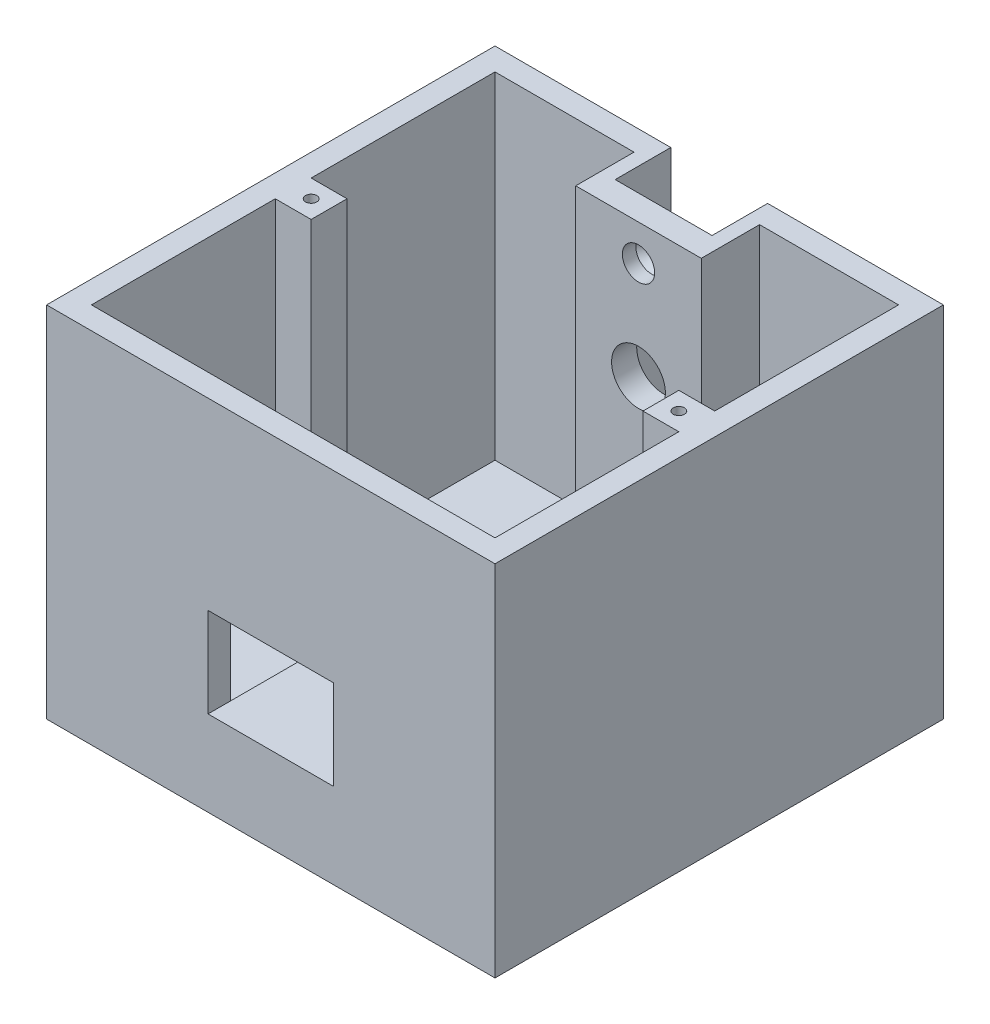
SolidWorks part; units mm, degrees
ref_plane "Front Plane" through (0, 0, 0) normal (0, 0, 1) x (1, 0, 0)
ref_plane "Top Plane" through (0, 0, 0) normal (0, 1, 0) x (1, 0, 0)
ref_plane "Right Plane" through (0, 0, 0) normal (1, 0, 0) x (0, 0, -1)
sketch "Sketch1" plane through (0, 0, 0) normal (0, 1, 0) x (1, 0, 0)
  line L1 (-25, -25) -> (25, -25)
  line L2 (-25, -25) -> (-25, 25)
  line L3 (-25, 25) -> (25, 25)
  line L4 (25, -25) -> (25, 25)
  line L5 (-25, -25) -> (25, 25) construction
  line L6 (-25, 25) -> (25, -25) construction
  point P0 (0, 0)
  dimension "D1" = 50
  dimension "D2" = 50
extrude "Boss-Extrude1" add sketch "Sketch1" along normal blind 40
shell "Shell1" thickness 2.5
sketch "Sketch2" plane through (0, 2.5, 0) normal (0, 1, 0) x (1, 0, 0)
  line L0 (22.5, 22.5) -> (-22.5, 22.5) construction
  line L1 (-7, 22.5) -> (7, 22.5)
  line L2 (-7, 22.5) -> (-7, -22.5)
  line L3 (-7, -22.5) -> (7, -22.5)
  line L4 (7, 22.5) -> (7, -22.5)
  line L5 (-22.5, -22.5) -> (22.5, -22.5) construction
  line L6 (22.5, 22.5) -> (-22.5, 22.5) construction
  point P10 (0, 22.5)
  point P11 (0, 22.5)
  dimension "D1" = 14
extrude "Boss-Extrude2" add sketch "Sketch2" along normal blind 7
sketch "Sketch4" plane through (0, 0, 0) normal (0, -1, 0) x (1, 0, 0)
  line L1 (-5.4, -15.1) -> (5.4, -15.1)
  line L2 (-5.4, -15.1) -> (-5.4, 15.1)
  line L3 (-5.4, 15.1) -> (5.4, 15.1)
  line L4 (5.4, -15.1) -> (5.4, 15.1)
  line L5 (-5.4, -15.1) -> (5.4, 15.1) construction
  line L6 (-5.4, 15.1) -> (5.4, -15.1) construction
  point P0 (0, 0)
  dimension "D1" = 30.2
  dimension "D2" = 10.8
extrude "Cut-Extrude1" cut sketch "Sketch4" against normal blind 6.2
sketch "Sketch5" plane through (0, 9.5, 0) normal (0, 1, 0) x (1, 0, 0)
  line L0 (-22.5, 0) -> (22.5, 0) construction
  line L1 (-22.5, 22.5) -> (-22.5, -22.5) construction
  line L2 (22.5, -22.5) -> (22.5, 22.5) construction
  line L3 (0, 11) -> (0, 0)
  line L4 (0, 0) -> (0, -11)
  point P6 (-35.5268, 3.9045)
  point P8 (0, 0)
  dimension "D1" = 11
hole_wizard "CSK SLOT for M1.6 Countersunk Flat Head Screw1" positions "Sketch6" profile "Sketch7" size "M1.6" standard "ISO" slot yes end condition through all
sketch "Sketch6" plane through (0, 9.5, 0) normal (0, 1, 0) x (1, 0, 0)
  point P0 (0, 11)
  point P3 (0, -11)
sketch "Sketch7" plane through (0, 9.5, -11) normal (1, 0, 0) x (0, 0, 1)
  line L0 (0, 0) -> (0, 9.5)
  line L1 (0, 9.5) -> (0.9, 9.5)
  line L2 (0.9, 9.5) -> (0.9, 2.9)
  line L3 (0.9, 2.9) -> (1.8, 2)
  line L4 (1.8, 2) -> (1.8, 0)
  line L6 (1.8, 0) -> (0, 0)
  line L7 (-0.9, 2.9) -> (-1.8, 2) construction
  line L11 (0, -6.35) -> (0, 107.95) construction
  dimension "Thru Hole Dia." = 1.8
  dimension "Thru Hole Depth" = 9.5
  dimension "C'Sink Dia." = 3.6
  dimension "C'Sink Angle" = 90
  dimension "Head Clearance" = 2
sketch "Sketch8" plane through (0, 2.5, 0) normal (0, 1, 0) x (1, 0, 0)
  line L0 (-22.5, 0) -> (22.5, 0) construction
  line L1 (19.5, -1.5) -> (16.5, -1.5)
  line L2 (19.5, -1.5) -> (19.5, 1.5)
  line L3 (19.5, 1.5) -> (16.5, 1.5)
  line L4 (16.5, -1.5) -> (16.5, 1.5)
  line L5 (19.5, -1.5) -> (16.5, 1.5) construction
  line L6 (19.5, 1.5) -> (16.5, -1.5) construction
  line L7 (22.5, -22.5) -> (22.5, 22.5) construction
  point P0 (18, 0)
  dimension "D1" = 3
  dimension "D2" = 3
  dimension "D3" = 3
extrude "Cut-Extrude2" [suppressed] cut sketch "Sketch8" against normal through all
sketch "Sketch9" plane through (-22.5, 0, 0) normal (1, 0, 0) x (0, 0, -1)
  line L0 (0, 2.5) -> (0, 40) construction
  line L1 (22.5, 2.5) -> (-22.5, 2.5) construction
  line L2 (22.5, 40) -> (-22.5, 40) construction
  line L4 (-7, 2.5) -> (7, 2.5)
  line L5 (-7, 2.5) -> (-7, 40)
  line L6 (-7, 40) -> (7, 40)
  line L7 (7, 2.5) -> (7, 40)
  point P8 (0, 21.25)
  point P11 (0, 40)
  dimension "D1" = 14
extrude "Boss-Extrude3" [suppressed] add sketch "Sketch9" along normal blind 10
sketch "Sketch10" plane through (-25, 0, 0) normal (-1, 0, 0) x (0, 0, 1)
  line L0 (0, 0) -> (0, 9.9)
  line L1 (-25, 0) -> (25, 0) construction
  line L2 (-25, 40) -> (25, 40) construction
  line L3 (-5.05, 40) -> (5.05, 40)
  line L4 (-5.05, 40) -> (-5.05, 9.9)
  line L5 (-5.05, 9.9) -> (5.05, 9.9)
  line L6 (5.05, 40) -> (5.05, 9.9)
  point P10 (0, 9.9)
  line M8 (25, 40) -> (-25, 40)
  dimension "D1" = 9.9
  dimension "D2" = 10.1
extrude "Cut-Extrude3" [suppressed] cut sketch "Sketch10" against normal blind 6.1 contours L6 L4 L5 M8
sketch "Sketch11" plane through (0, 9.5, 0) normal (0, 1, 0) x (1, 0, 0)
  line L0 (-7, 22.5) -> (-7, -22.5) construction
  line L1 (-7, 6) -> (7, 6)
  line L2 (-7, 6) -> (-7, -6)
  line L3 (-7, -6) -> (7, -6)
  line L4 (7, 6) -> (7, -6)
  line L5 (7, -22.5) -> (7, 22.5) construction
  dimension "D1" = 5
  dimension "D2" = 5
extrude "Cut-Extrude4" cut sketch "Sketch11" against normal up to surface (7 mm away) up to face at (-14.75, 2.5, 0)
sketch "Sketch12" [suppressed] plane through (-12.5, 0, 0) normal (1, 0, 0) x (0, 0, -1)
  line L0 (0, 40) -> (0, 25)
  line L1 (7, 40) -> (-7, 40) construction
  line L2 (0, 25) -> (0, 14)
  point P5 (0, 36)
  dimension "D1" = 15
  dimension "D2" = 11
  dimension "D3" = 11
hole_wizard "CSK SLOT for M1.6 Countersunk Flat Head Screw2" [suppressed] positions "Sketch13" profile "Sketch14" size "M1.6" standard "ISO"
sketch "Sketch13" [suppressed] plane through (-12.5, 0, 0) normal (1, 0, 0) x (0, 0, -1)
  point P0 (0, 36)
  point P8 (0, 14)
sketch "Sketch14" plane through (-12.5, 36, 0) normal (0, 1, 0) x (0, 0, -1)
  line L0 (0, 0) -> (0, 12.5)
  line L1 (0, 12.5) -> (0.9, 12.5)
  line L2 (0.9, 12.5) -> (0.9, 0.9)
  line L3 (0.9, 0.9) -> (1.8, 0)
  line L5 (1.8, 0) -> (0, 0)
  line L6 (-0.9, 0.9) -> (-1.8, 0) construction
  line L11 (0, -6.35) -> (0, 107.95) construction
  dimension "Thru Hole Dia." = 1.8
  dimension "Thru Hole Depth" = 12.5
  dimension "Near C'Sink Dia." = 3.6
  dimension "Near C'Sink Angle" = 90
sketch "Sketch15" plane through (0, 9.5, 0) normal (0, 1, 0) x (1, 0, 0)
  line L1 (-22.5, -22.5) -> (22.5, -22.5) construction
  line L6 (-2, -18.5) -> (2, -18.5)
  line L7 (-2, -18.5) -> (-2, -22.5)
  line L8 (-2, -22.5) -> (2, -22.5)
  line L9 (2, -18.5) -> (2, -22.5)
  point P7 (0, -22.5)
  point P9 (0, -22.5)
  dimension "D1" = 4
  dimension "D2" = 4
extrude "Boss-Extrude4" [suppressed] add sketch "Sketch15" along normal blind 37.5
ref_plane "Plane1" through (0, 0, 0) normal (0, 0, 1) x (1, 0, 0)
hole_wizard "M1.6 Tapped Hole1" [suppressed] positions "Sketch16" profile "Sketch17" tap size "M1.6" standard "ISO"
sketch "Sketch16" [suppressed] plane through (0, 50, 0) normal (0, 1, 0) x (1, 0, 0)
  line L0 (-2, -22.5) -> (2, -18.5)
  point P0 (0, -20.5)
  point P9 (0, -20.5)
sketch "Sketch17" plane through (0, 50, 20.5) normal (1, 0, 0) x (0, 0, 1)
  line L0 (0, 0) -> (0, 5.3755)
  line L1 (0, 5.3755) -> (0.625, 5)
  line L2 (0.625, 5) -> (0.625, 0)
  line L5 (0.625, 0) -> (0, 0)
  line L10 (0, 5.3755) -> (-0.625, 5) construction
  line L11 (0, -6.35) -> (0, 107.95) construction
  dimension "Tap Drill Dia." = 1.25
  dimension "Tap Drill Depth" = 5
  dimension "Drill Angle" = 118
cosmetic thread "Hole Thread1" [suppressed] parameters "D1"=3.2, "D2"=1.6
sketch "Sketch18" [suppressed] plane through (0, 40, 0) normal (0, 1, 0) x (1, 0, 0)
  line L8 (-12.5, -7) -> (-12.5, 7) construction
  line L9 (-18.9, 5.05) -> (-12.5, 5.05)
  line L10 (-18.9, 5.05) -> (-18.9, 2.05)
  line L11 (-18.9, 2.05) -> (-12.5, 2.05)
  line L12 (-12.5, 5.05) -> (-12.5, 2.05)
  dimension "D1" = 3
extrude "Cut-Extrude5" [suppressed] cut sketch "Sketch18" against normal blind 2
mirror "Mirror2" [suppressed] about plane through (0, 0, 0) normal (0, 0, 1)
cosmetic thread "Hole Thread2" [suppressed] parameters "D1"=3.2, "D2"=1.6
sketch "Sketch19" plane through (0, 0, -22.5) normal (0, 0, 1) x (1, 0, 0)
  line L0 (22.5, 40) -> (-22.5, 40) construction
  line L1 (-7, 9.5) -> (7, 9.5)
  line L2 (-7, 9.5) -> (-7, 40)
  line L3 (-7, 40) -> (7, 40)
  line L4 (7, 9.5) -> (7, 40)
extrude "Boss-Extrude5" add sketch "Sketch19" along normal blind 6.5
sketch "Sketch20" plane through (0, 0, -25) normal (0, 0, -1) x (-1, 0, 0)
  line L0 (-25, 40) -> (25, 40) construction
  line L1 (0, 40) -> (0, 25)
  line L3 (5.4, 40.1) -> (-5.4, 40.1)
  line L4 (5.4, 40.1) -> (5.4, 9.9)
  line L5 (5.4, 9.9) -> (-5.4, 9.9)
  line L6 (-5.4, 40.1) -> (-5.4, 9.9)
  line L7 (5.4, 40.1) -> (-5.4, 9.9) construction
  line L8 (5.4, 9.9) -> (-5.4, 40.1) construction
  dimension "D1" = 15
  dimension "D2" = 30.2
  dimension "D3" = 10.8
extrude "Cut-Extrude6" cut sketch "Sketch20" against normal blind 6.2
sketch "Sketch21" plane through (0, 0, -16) normal (0, 0, 1) x (1, 0, 0)
  line L0 (7, 40) -> (-7, 40) construction
  line L1 (0, 40) -> (0, 25)
  line L2 (0, 25) -> (0, 14)
  point P2 (0, 36)
  dimension "D1" = 15
  dimension "D2" = 11
  dimension "D3" = 11
hole_wizard "CSK SLOT for M1.6 Countersunk Flat Head Screw3" positions "Sketch26" profile "Sketch27" size "M1.6" standard "ISO" slot yes
sketch "Sketch26" plane through (0, 0, -16) normal (0, 0, 1) x (1, 0, 0)
  point P0 (0, 36)
  point P3 (0, 14)
sketch "Sketch27" plane through (0, 36, -16) normal (1, 0, 0) x (0, -1, 0)
  line L0 (0, 0) -> (0, 40.5408)
  line L1 (0, 40.5408) -> (0.9, 40)
  line L2 (0.9, 40) -> (0.9, 2.4)
  line L3 (0.9, 2.4) -> (1.8, 1.5)
  line L4 (1.8, 1.5) -> (1.8, 0)
  line L6 (1.8, 0) -> (0, 0)
  line L7 (-0.9, 2.4) -> (-1.8, 1.5) construction
  line L10 (0, 40.5408) -> (-0.9, 40) construction
  line L11 (0, -6.35) -> (0, 107.95) construction
  dimension "Hole Dia." = 1.8
  dimension "Hole Depth" = 40
  dimension "C'Sink Dia." = 3.6
  dimension "C'Sink Angle" = 90
  dimension "Drill Angle" = 118
  dimension "Head Clearance" = 1.5
sketch "Sketch28" plane through (0, 0, -18.8) normal (0, 0, -1) x (-1, 0, 0)
  line L1 (-5.4, 40) -> (-2.4, 40)
  line L2 (-5.4, 40) -> (-5.4, 37)
  line L3 (-5.4, 37) -> (-2.4, 37)
  line L4 (-2.4, 40) -> (-2.4, 37)
  dimension "D1" = 3
  dimension "D2" = 3
extrude "Cut-Extrude7" [suppressed] cut sketch "Sketch28" against normal up to next
sketch "Sketch30" plane through (0, 2.5, 0) normal (0, 1, 0) x (1, 0, 0)
  line L0 (-22.5, 22.5) -> (-22.5, -22.5) construction
  line L2 (-22.5, 2) -> (-18.5, 2)
  line L3 (-22.5, 2) -> (-22.5, -2)
  line L4 (-22.5, -2) -> (-18.5, -2)
  line L5 (-18.5, 2) -> (-18.5, -2)
  point P8 (-22.5, 0)
  dimension "D1" = 4
  dimension "D2" = 4
extrude "Boss-Extrude6" add sketch "Sketch30" along normal blind 37.5
hole_wizard "M1.6 Tapped Hole2" positions "Sketch31" profile "Sketch32" tap size "M1.6" standard "ISO"
sketch "Sketch31" plane through (0, 40, 0) normal (0, 1, 0) x (1, 0, 0)
  line L0 (-22.5, 0) -> (22.5, 0) construction
  line L1 (-18.5, -2) -> (-22.5, 2)
  point P0 (-20.5, 0)
  point P11 (-20.5, 0)
sketch "Sketch32" plane through (-20.5, 40, 0) normal (1, 0, 0) x (0, 0, 1)
  line L0 (0, 0) -> (0, 5.3755)
  line L1 (0, 5.3755) -> (0.625, 5)
  line L2 (0.625, 5) -> (0.625, 0)
  line L5 (0.625, 0) -> (0, 0)
  line L10 (0, 5.3755) -> (-0.625, 5) construction
  line L11 (0, -6.35) -> (0, 107.95) construction
  dimension "Tap Drill Dia." = 1.25
  dimension "Tap Drill Depth" = 5
  dimension "Drill Angle" = 118
cosmetic thread "Hole Thread3" parameters "D1"=3.2, "D2"=1.6
ref_plane "Plane2" through (0, 0, 0) normal (1, 0, 0) x (0, 0, -1)
mirror "Mirror3" about plane through (0, 0, 0) normal (1, 0, 0) of "M1.6 Tapped Hole2", "Boss-Extrude6"
cosmetic thread "Hole Thread4" parameters "D1"=3.2, "D2"=1.6
sketch "Sketch33" plane through (0, 0, -18.8) normal (0, 0, -1) x (-1, 0, 0)
  circle A0 centre (0, 25) radius 3
  dimension "D1" = 6
extrude "Cut-Extrude8" cut sketch "Sketch33" against normal up to next
sketch "Sketch34" plane through (0, 0, 25) normal (0, 0, 1) x (1, 0, 0)
  circle A0 centre (0, 14) radius 4
  dimension "D1" = 8
extrude "Cut-Extrude9" [suppressed] cut sketch "Sketch34" against normal up to next
sketch "Sketch35" plane through (0, 0, 22.5) normal (0, 0, -1) x (-1, 0, 0)
  line L0 (-7, 9.5) -> (-7, 19.5)
  line L1 (-7, 19.5) -> (7, 19.5)
  line L2 (7, 19.5) -> (7, 9.5)
  line L3 (-7, 9.5) -> (7, 9.5)
  dimension "D1" = 10
extrude "Cut-Extrude10" cut sketch "Sketch35" against normal blind 10
